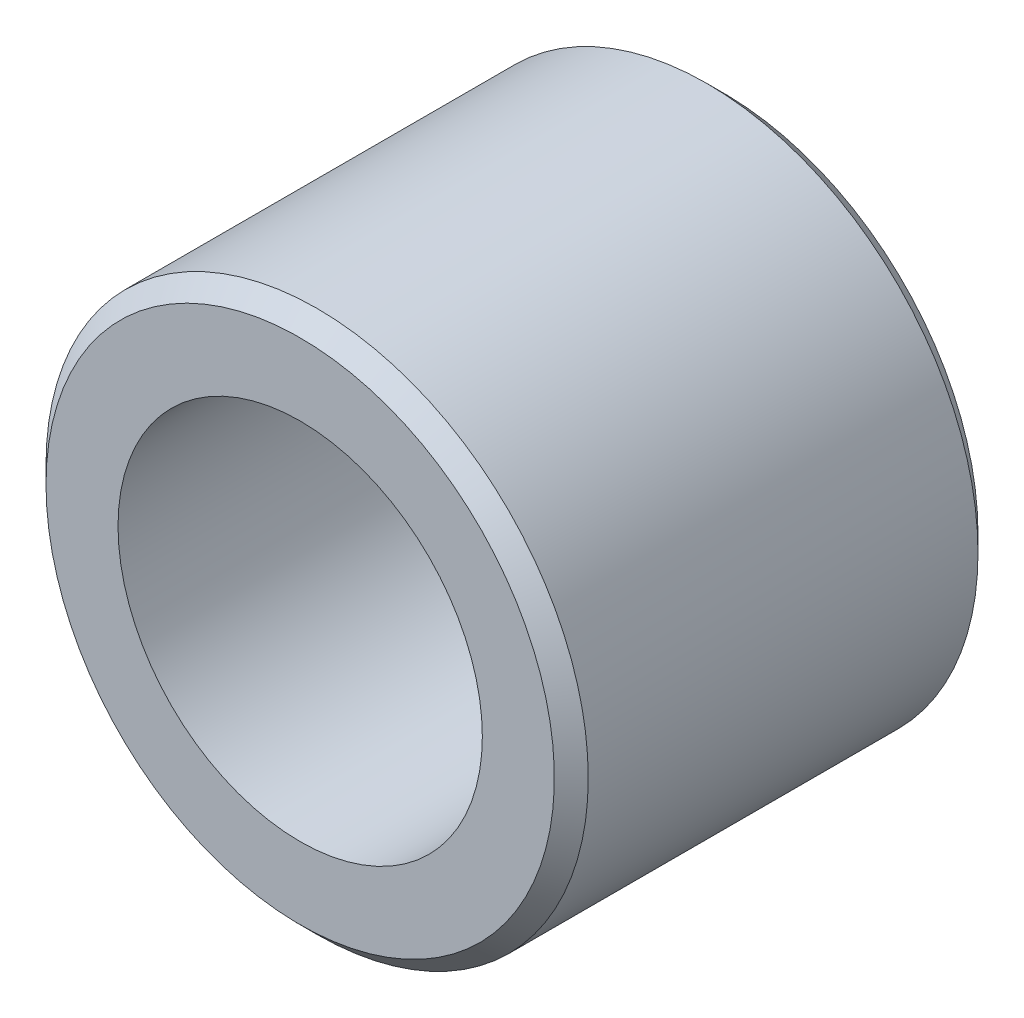
SolidWorks part; units mm, degrees
ref_plane "Front Plane" through (0, 0, 0) normal (0, 0, 1) x (1, 0, 0)
ref_plane "Top Plane" through (0, 0, 0) normal (0, 1, 0) x (1, 0, 0)
ref_plane "Right Plane" through (0, 0, 0) normal (1, 0, 0) x (0, 0, -1)
sketch "Sketch1" plane through (0, 0, 0) normal (0, 0, 1) x (1, 0, 0)
  circle A0 centre (0, 0) radius 6.4
  circle A1 centre (0, 0) radius 4.3
  dimension "D1" = 2.1
  dimension "D2" = 8.6
extrude "Boss-Extrude1" add sketch "Sketch1" along normal blind 10
chamfer "Chamfer1" distance 0.4 angle 45 2 edges at (6.4, 0, 10) (6.4, 0, 0)
